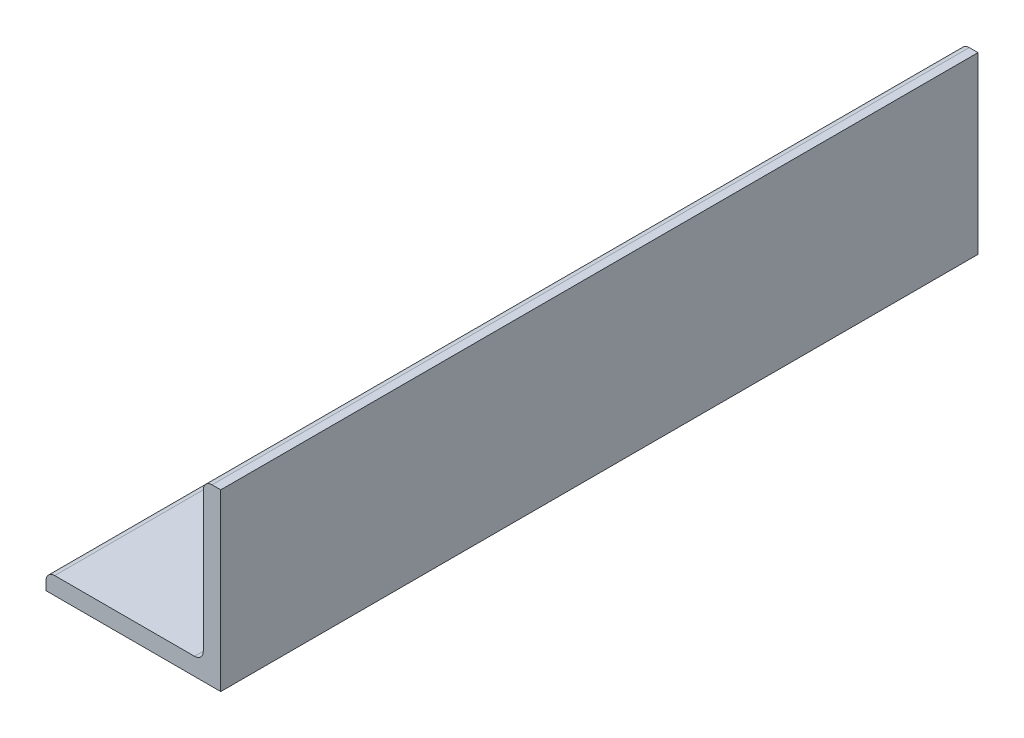
SolidWorks part; units mm, degrees
material "ASTM A36 Steel"
ref_plane "Front Plane" through (0, 0, 0) normal (0, 0, 1) x (1, 0, 0)
ref_plane "Top Plane" through (0, 0, 0) normal (0, 1, 0) x (1, 0, 0)
ref_plane "Right Plane" through (0, 0, 0) normal (1, 0, 0) x (0, 0, -1)
sketch "Sketch1" plane through (0, 0, 0) normal (0, 0, 1) x (1, 0, 0)
  line L0 (-135.6009, 27) -> (-135.6009, -3)
  line L1 (-135.6009, -3) -> (-165.6009, -3)
  line L2 (-165.6009, -3) -> (-165.6009, -1.5)
  line L3 (-164.1009, 0) -> (-140.1009, 0)
  line L4 (-138.6009, 1.5) -> (-138.6009, 25.5)
  line L5 (-137.1009, 27) -> (-135.6009, 27)
  arc A0 (-138.6009, 25.5) -> (-137.1009, 27) centre (-137.1009, 25.5) cw
  arc A1 (-140.1009, 0) -> (-138.6009, 1.5) centre (-140.1009, 1.5) ccw
  arc A2 (-165.6009, -1.5) -> (-164.1009, 0) centre (-164.1009, -1.5) cw
  point P9 (-138.6009, 27)
  point P14 (-165.6009, 0)
  dimension "D5" = 1.5
  dimension "D1" = 3
  dimension "D2" = 30
  dimension "D3" = 30
  dimension "D4" = 3
extrude "Boss-Extrude1" add sketch "Sketch1" along normal blind 130
